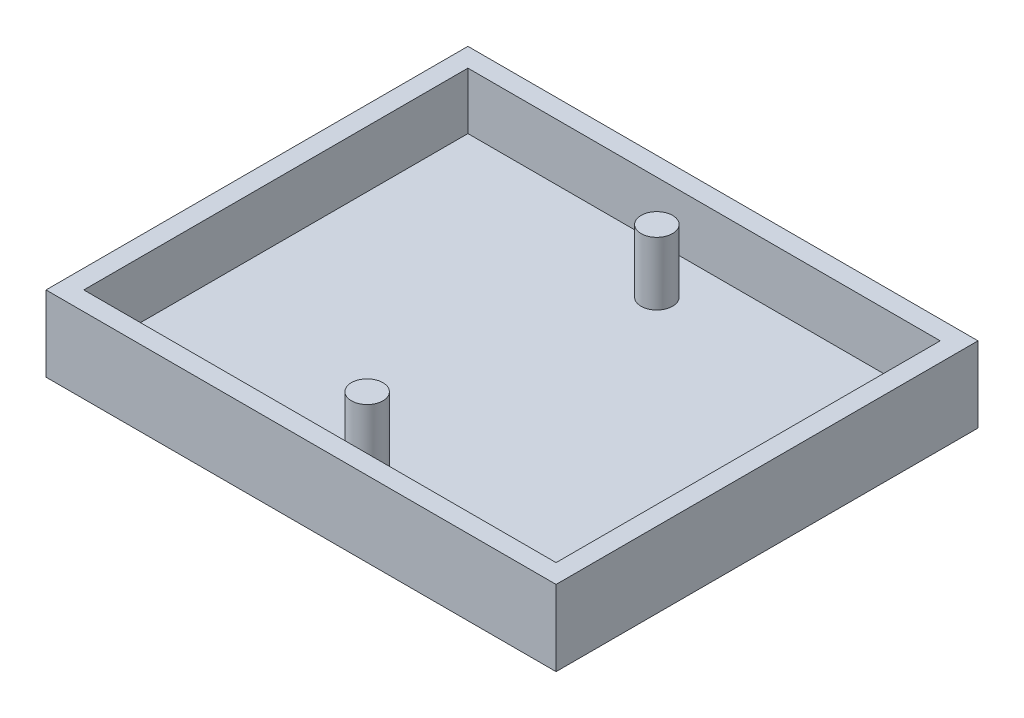
SolidWorks part; units mm, degrees
ref_plane "Plan de face" through (0, 0, 0) normal (0, 0, 1) x (1, 0, 0)
ref_plane "Plan de dessus" through (0, 0, 0) normal (0, 1, 0) x (1, 0, 0)
ref_plane "Plan de droite" through (0, 0, 0) normal (1, 0, 0) x (0, 0, -1)
sketch "Esquisse1" plane through (0, 0, 0) normal (0, 1, 0) x (1, 0, 0)
  line L0 (37.5, 30.5) -> (37.5, 32) construction
  line L1 (0, 0) -> (37.5, 0)
  line L2 (0, 0) -> (0, 30.5)
  line L3 (0, 30.5) -> (37.5, 30.5)
  line L4 (37.5, 0) -> (37.5, 30.5)
  line L5 (37.5, 32) -> (39, 32) construction
  line L6 (0, 0) -> (0, -1.5) construction
  line L7 (0, -1.5) -> (-1.5, -1.5) construction
  line L9 (-1.5, -1.5) -> (39, -1.5)
  line L10 (-1.5, -1.5) -> (-1.5, 32)
  line L11 (-1.5, 32) -> (39, 32)
  line L12 (39, -1.5) -> (39, 32)
  dimension "D1" = 30.5
  dimension "D2" = 37.5
  dimension "D3" = 33.5
  dimension "D4" = 40.5
extrude "Boss.-Extru.1" add sketch "Esquisse1" along normal blind 4.5
sketch "Esquisse2" plane through (0, 0, 0) normal (0, -1, 0) x (1, 0, 0)
  line L1 (-1.5, 1.5) -> (39, 1.5)
  line L2 (-1.5, 1.5) -> (-1.5, -32)
  line L3 (-1.5, -32) -> (39, -32)
  line L4 (39, 1.5) -> (39, -32)
  dimension "D1" = 33.5
  dimension "D2" = 40.5
extrude "Boss.-Extru.2" add sketch "Esquisse2" along normal blind 1.5
sketch "Esquisse3" plane through (0, 0, 0) normal (0, 1, 0) x (1, 0, 0)
  line L0 (18.75, 30.5) -> (18.75, 0) construction
  line L1 (37.5, 30.5) -> (0, 30.5) construction
  line L2 (18.75, 15.25) -> (18.75, 26.75) construction
  line L3 (18.75, 15.25) -> (18.75, 3.75) construction
  circle A0 centre (18.75, 26.75) radius 1.25
  circle A1 centre (18.75, 3.75) radius 1.25
extrude "Boss.-Extru.3" add sketch "Esquisse3" along normal blind 5
